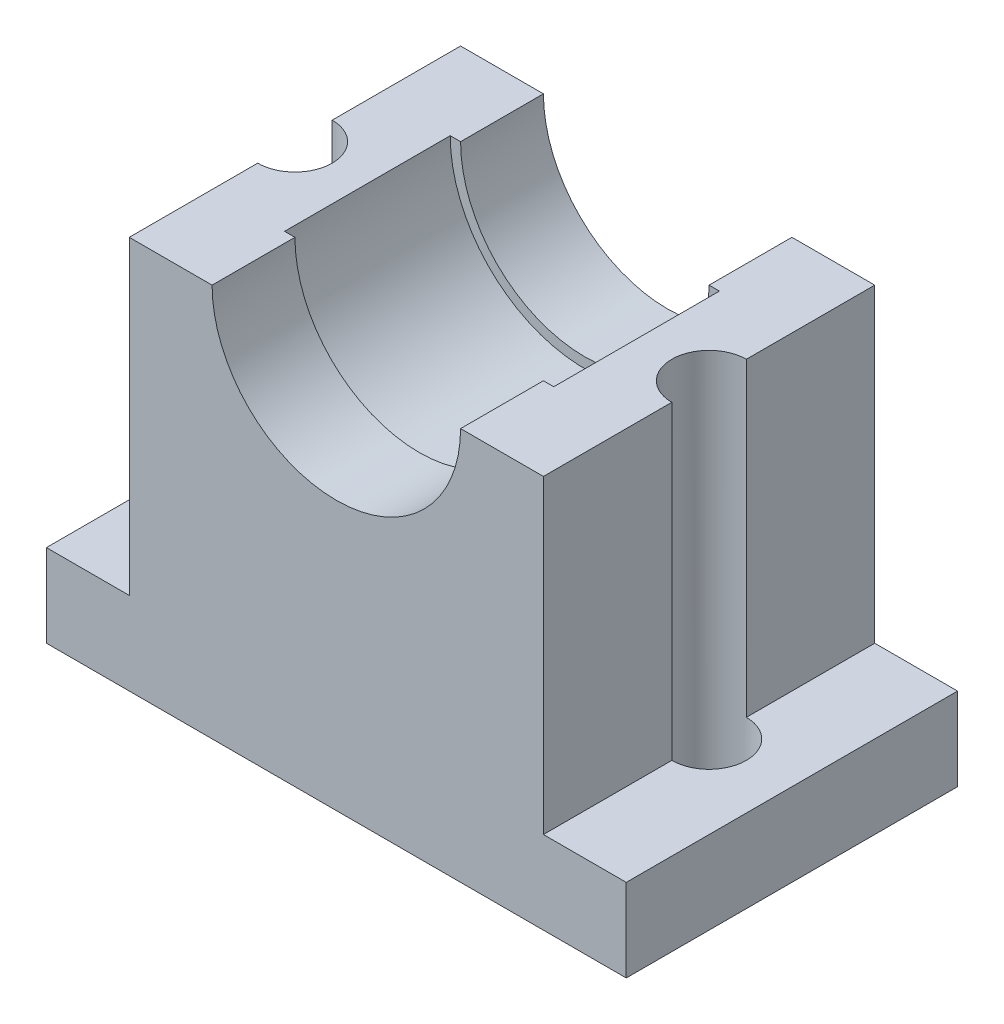
SolidWorks part; units mm, degrees
ref_plane "Front Plane" through (0, 0, 0) normal (0, 0, 1) x (1, 0, 0)
ref_plane "Top Plane" through (0, 0, 0) normal (0, 1, 0) x (1, 0, 0)
ref_plane "Right Plane" through (0, 0, 0) normal (1, 0, 0) x (0, 0, -1)
sketch "Sketch1" plane through (0, 0, 0) normal (0, 1, 0) x (1, 0, 0)
  line L1 (-70, -40) -> (70, -40)
  line L2 (-70, -40) -> (-70, 40)
  line L3 (-70, 40) -> (70, 40)
  line L4 (70, -40) -> (70, 40)
  line L5 (-70, -40) -> (70, 40) construction
  line L6 (-70, 40) -> (70, -40) construction
  point P0 (0, 0)
  dimension "D1" = 140
  dimension "D2" = 80
extrude "Boss-Extrude1" add sketch "Sketch1" along normal blind 20
sketch "Sketch2" plane through (0, 0, 40) normal (0, 0, 1) x (1, 0, 0)
  line L5 (-70, 20) -> (70, 20) construction
  line L6 (30, 94.8837) -> (50, 94.8837)
  line L7 (-50, 20) -> (50, 20)
  line L8 (-50, 20) -> (-50, 94.8837)
  line L9 (-50, 94.8837) -> (-30, 94.8837)
  line L10 (50, 20) -> (50, 94.8837)
  arc A0 (-30, 94.8837) -> (30, 94.8837) centre (0, 94.8837) ccw
  dimension "D1" = 20
  dimension "D2" = 20
extrude "Boss-Extrude2" add sketch "Sketch2" against normal through all
sketch "Sketch3" plane through (0, 94.8837, 0) normal (0, 1, 0) x (1, 0, 0)
  line L0 (-30, 40) -> (-30, -40) construction
  line L1 (-30, -20) -> (-32.5, -20)
  line L2 (-30, -20) -> (-30, 20)
  line L3 (-30, 20) -> (-32.5, 20)
  line L4 (-32.5, -20) -> (-32.5, 20)
  line L5 (0, -29.576) -> (0, 40.6402) construction
  point P9 (-30, 0)
  dimension "D1" = 2.5
revolve "Cut-Revolve1" cut sketch "Sketch3" angle 360 about L5
sketch "Sketch4" plane through (0, 94.8837, 0) normal (0, 1, 0) x (1, 0, 0)
  line L0 (50, 40) -> (50, -40) construction
  circle A0 centre (50, 0) radius 9
  dimension "D1" = 18
extrude "Cut-Extrude1" cut sketch "Sketch4" against normal through all
mirror "Mirror1" about plane through (0, 0, 0) normal (1, 0, 0) of "Cut-Extrude1"
